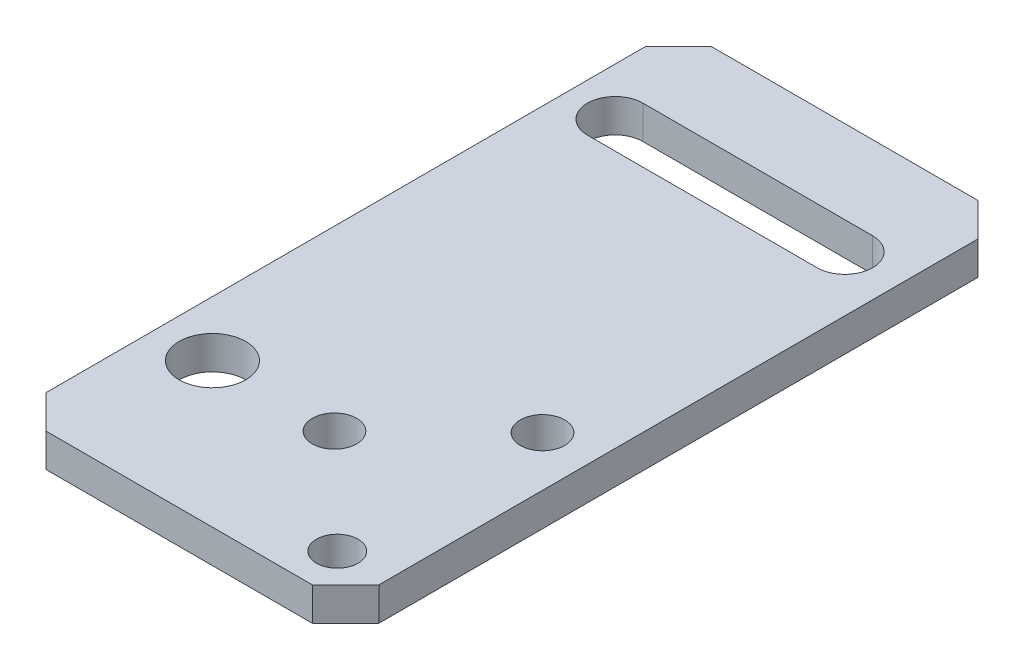
SolidWorks part; units mm, degrees
ref_plane "Alzado" through (0, 0, 0) normal (0, 0, 1) x (1, 0, 0)
ref_plane "Planta" through (0, 0, 0) normal (0, 1, 0) x (1, 0, 0)
ref_plane "Vista lateral" through (0, 0, 0) normal (1, 0, 0) x (0, 0, -1)
sketch "Croquis1" plane through (0, 0, 0) normal (0, 1, 0) x (1, 0, 0)
  line L0 (0, 0) -> (0, 34.7658) construction
  line L1 (-15, -30) -> (15, -30)
  line L2 (-15, -30) -> (-15, 30)
  line L3 (-15, 30) -> (15, 30)
  line L4 (15, -30) -> (15, 30)
  line L5 (-15, -30) -> (15, 30) construction
  line L6 (-15, 30) -> (15, -30) construction
  line L7 (10.5, -7.75) -> (10.5, -26.25) construction
  line L8 (-10.7, 17.5) -> (10, 17.5)
  line L9 (-10.7, 22.5) -> (10, 22.5)
  arc A0 (-10.7, 22.5) -> (-10.7, 17.5) centre (-10.7, 20) ccw
  arc A1 (10, 17.5) -> (10, 22.5) centre (10, 20) ccw
  circle A4 centre (-10, -17) radius 3
  circle A5 centre (1, -17) radius 2
  circle A6 centre (10.5, -7.75) radius 2
  circle A7 centre (10.5, -26.25) radius 1.8784
  point P0 (0, 0)
  point P26 (10.5, -17)
  dimension "D5" = 5
  dimension "D9" = 6
  dimension "D12" = 4
  dimension "D15" = 4
  dimension "D1" = 30
  dimension "D2" = 60
  dimension "D3" = 10.7
  dimension "D4" = 10
  dimension "D6" = 10
  dimension "D8" = 5
  dimension "D10" = 13
  dimension "D11" = 11
  dimension "D13" = 9.5
  dimension "D14" = 18.5
extrude "Saliente-Extruir1" add sketch "Croquis1" along normal blind 3
chamfer "Chaflán1" distance 3 angle 45 4 edges at (15, 1.5, 30) (-15, 1.5, 30) (15, 1.5, -30) (-15, 1.5, -30)
